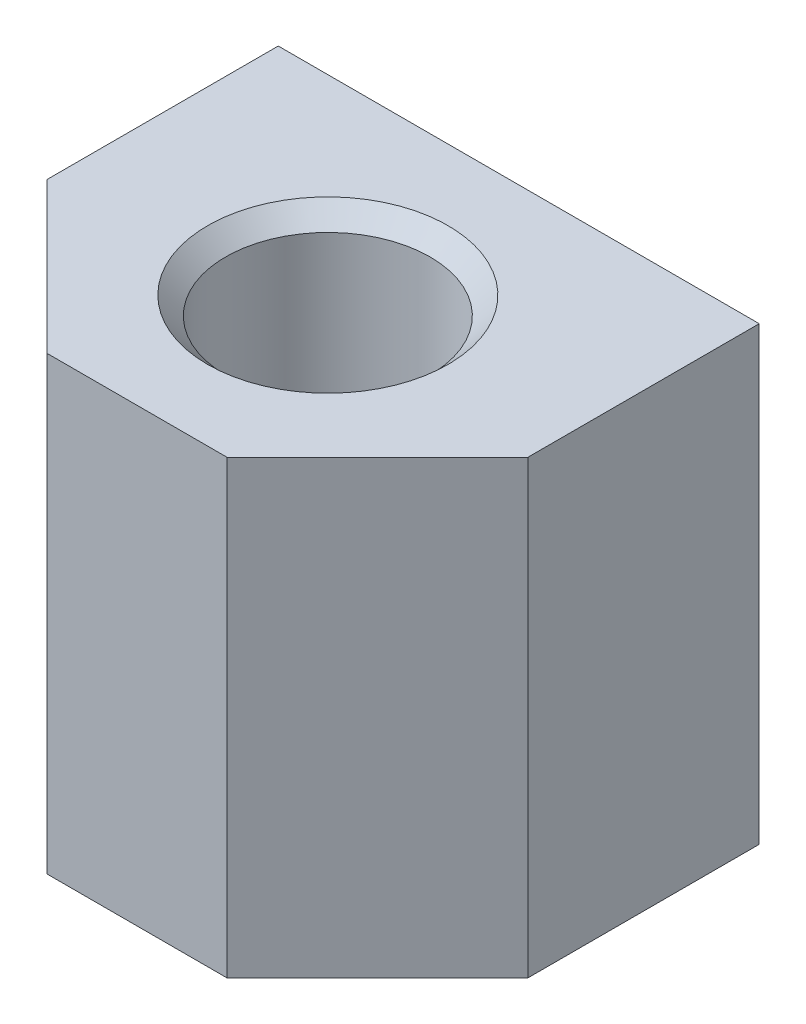
SolidWorks part; units mm, degrees
material "AISI 1020"
ref_plane "Plano frontal" through (0, 0, 0) normal (0, 0, 1) x (1, 0, 0)
ref_plane "Plano superior" through (0, 0, 0) normal (0, 1, 0) x (1, 0, 0)
ref_plane "Plano direito" through (0, 0, 0) normal (1, 0, 0) x (0, 0, -1)
sketch "Esboço1" plane through (0, 0, 0) normal (0, 1, 0) x (1, 0, 0)
  line L0 (0, 0) -> (7.3323, 0) construction
  line L1 (7.3323, 0) -> (3.6662, 6.35) construction
  line L2 (3.6662, 6.35) -> (-3.6662, 6.35)
  line L3 (-3.6662, 6.35) -> (-7.3323, 0) construction
  line L4 (-7.3323, 0) -> (-3.6662, -6.35) construction
  line L5 (-3.6662, -6.35) -> (3.6662, -6.35) construction
  line L6 (3.6662, -6.35) -> (7.3323, 0) construction
  line L7 (3.6662, 6.35) -> (8, 6.35)
  line L8 (8, 6.35) -> (8, -6.35)
  line L9 (8, -6.35) -> (-8, -6.35)
  line L10 (0, -6.35) -> (0, 0) construction
  line L11 (-3.6662, 6.35) -> (-8, 6.35)
  line L12 (-8, 6.35) -> (-8, -6.35)
  circle A0 centre (0, 0) radius 6.35 construction
  dimension "D1" = 6.35
  dimension "D2" = 12.7
  dimension "D3" = 8
extrude "Ressalto-extrusão1" add sketch "Esboço1" along normal mid plane 15
hole_wizard "Furo roscado de M81" positions "Esboço4" profile "Esboço5" tap size "M8" standard "Din" end condition through all
sketch "Esboço4" plane through (0, 7.5, 0) normal (0, 1, 0) x (1, 0, 0)
  point P0 (0, 0)
sketch "Esboço5" plane through (0, 7.5, 0) normal (1, 0, 0) x (0, 0, 1)
  line L0 (0, 0) -> (0, 15)
  line L1 (0, 15) -> (4, 15)
  line L2 (3.4, 14.4) -> (3.4, 0.6)
  line L3 (3.4, 0.6) -> (4, 0)
  line L5 (4, 0) -> (0, 0)
  line L6 (-3.4, 0.6) -> (-4, 0) construction
  line L7 (4, 15) -> (3.4, 14.4)
  line L8 (-4, 15) -> (-3.4, 14.4) construction
  line L11 (0, -6.35) -> (0, 107.95) construction
  dimension "Thru Tap Drill Dia." = 6.8
  dimension "Thru Tap Drill Depth" = 15
  dimension "Near C'Sink Dia." = 8
  dimension "Near C'Sink Angle" = 90
  dimension "Far C'Sink Dia." = 8
  dimension "Far C'Sink Angle" = 90
cosmetic thread "Rosca de furo1" parameters "D2"=8
hole_wizard "Furo roscado de M31" positions "Esboço7" profile "Esboço6" tap size "M3" standard "Din"
sketch "Esboço7" plane through (0, 0, -6.35) normal (0, 0, -1) x (-1, 0, 0)
  line L0 (0, 0) -> (0, 7.5) construction
  line L1 (-8, 7.5) -> (8, 7.5) construction
  line L3 (0, 0) -> (-6, 0) construction
  line L5 (-8, 7.5) -> (-8, -7.5) construction
  point P0 (-6, 0)
  point P16 (6, 0)
  dimension "D1" = 2
sketch "Esboço6" plane through (6, 0, -6.35) normal (1, 0, 0) x (0, 1, 0)
  line L0 (0, 0) -> (0, 8.2511)
  line L1 (0, 8.2511) -> (1.25, 7.5)
  line L2 (1.25, 7.5) -> (1.25, 0.275)
  line L3 (1.25, 0.275) -> (1.525, 0)
  line L5 (1.525, 0) -> (0, 0)
  line L6 (-1.25, 0.275) -> (-1.525, 0) construction
  line L10 (0, 8.2511) -> (-1.25, 7.5) construction
  line L11 (0, -6.35) -> (0, 107.95) construction
  dimension "Tap Drill Dia." = 2.5
  dimension "Tap Drill Depth" = 7.5
  dimension "Near C'Sink Dia." = 3.05
  dimension "Near C'Sink Angle" = 90
  dimension "Drill Angle" = 118
cosmetic thread "Rosca de furo2" parameters "D1"=6, "D2"=3
cosmetic thread "Rosca de furo3" parameters "D1"=6, "D2"=3
chamfer "Chanfro1" distance 5 angle 45 2 edges at (-8, 0, 6.35) (8, 0, 6.35)
